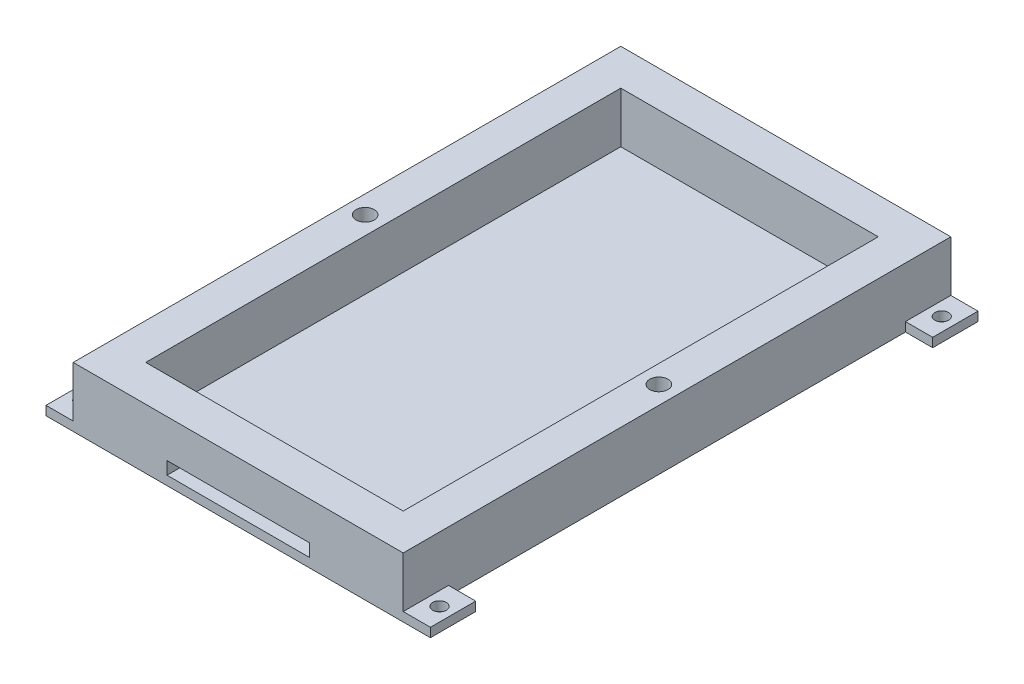
SolidWorks part; units mm, degrees
ref_plane "Plano frontal" through (0, 0, 0) normal (0, 0, 1) x (1, 0, 0)
ref_plane "Plano superior" through (0, 0, 0) normal (0, 1, 0) x (1, 0, 0)
ref_plane "Plano direito" through (0, 0, 0) normal (1, 0, 0) x (0, 0, -1)
sketch "Esboço1" plane through (0, 0, 0) normal (0, 1, 0) x (1, 0, 0)
  line L1 (-14.2, 26.2) -> (14.2, 26.2)
  line L2 (-14.2, 26.2) -> (-14.2, -26.2)
  line L3 (-14.2, -26.2) -> (14.2, -26.2)
  line L4 (14.2, 26.2) -> (14.2, -26.2)
  line L5 (-14.2, 26.2) -> (14.2, -26.2) construction
  line L6 (-14.2, -26.2) -> (14.2, 26.2) construction
  line L7 (-18.2, 30.2) -> (18.2, 30.2)
  line L8 (-18.2, 30.2) -> (-18.2, -30.2)
  line L9 (-18.2, -30.2) -> (18.2, -30.2)
  line L10 (18.2, 30.2) -> (18.2, -30.2)
  line L11 (-18.2, 30.2) -> (18.2, -30.2) construction
  line L12 (-18.2, -30.2) -> (18.2, 30.2) construction
  point P0 (0, 0)
  point P6 (0, 0)
  dimension "D1" = 52.4
  dimension "D2" = 28.4
  dimension "D3" = 60.4
  dimension "D4" = 36.4
extrude "Ressalto-extrusão1" add sketch "Esboço1" along normal blind 6.6
sketch "Esboço2" plane through (0, 0, 0) normal (0, 1, 0) x (1, 0, 0)
  line L1 (14.2, -26.2) -> (-14.2, -26.2)
  line L2 (14.2, -26.2) -> (14.2, 26.2)
  line L3 (14.2, 26.2) -> (-14.2, 26.2)
  line L4 (-14.2, -26.2) -> (-14.2, 26.2)
  line L5 (14.2, -26.2) -> (-14.2, 26.2) construction
  line L6 (14.2, 26.2) -> (-14.2, -26.2) construction
  point P0 (0, 0)
extrude "Ressalto-extrusão2" add sketch "Esboço2" along normal blind 1
sketch "Esboço3" plane through (0, 0, 30.2) normal (0, 0, 1) x (1, 0, 0)
  line L0 (-14.2, 1) -> (14.2, 1) construction
  line L1 (7.85, 1) -> (-7.85, 1)
  line L2 (7.85, 1) -> (7.85, 2.4)
  line L3 (7.85, 2.4) -> (-7.85, 2.4)
  line L4 (-7.85, 1) -> (-7.85, 2.4)
  dimension "D1" = 7.85
  dimension "D2" = 15.7
  dimension "D3" = 1.4
sketch "Esboço5" plane through (0, 0, 0) normal (0, 1, 0) x (1, 0, 0)
  line L1 (-18.2, 30.2) -> (-21.2, 30.2)
  line L2 (-18.2, 30.2) -> (-18.2, 25.2)
  line L3 (-18.2, 25.2) -> (-21.2, 25.2)
  line L4 (-21.2, 30.2) -> (-21.2, 25.2)
  line L5 (-18.2, -30.2) -> (-21.2, -30.2)
  line L6 (-18.2, -30.2) -> (-18.2, -25.2)
  line L7 (-18.2, -25.2) -> (-21.2, -25.2)
  line L8 (-21.2, -30.2) -> (-21.2, -25.2)
  line L9 (18.2, -30.2) -> (21.2, -30.2)
  line L10 (18.2, -30.2) -> (18.2, -25.2)
  line L11 (18.2, -25.2) -> (21.2, -25.2)
  line L12 (21.2, -30.2) -> (21.2, -25.2)
  line L13 (18.2, 30.2) -> (21.2, 30.2)
  line L14 (18.2, 30.2) -> (18.2, 25.2)
  line L15 (18.2, 25.2) -> (21.2, 25.2)
  line L16 (21.2, 30.2) -> (21.2, 25.2)
  circle A0 centre (-19.7, 27.7) radius 0.75
  circle A1 centre (19.7, 27.7) radius 0.75
  circle A2 centre (19.7, -27.7) radius 0.75
  circle A3 centre (-19.7, -27.7) radius 0.75
  point P30 (19.7, -27.7)
  dimension "D9" = 1.5
  dimension "D1" = 3
  dimension "D2" = 5
  dimension "D3" = 3
  dimension "D4" = 5
  dimension "D5" = 3
  dimension "D6" = 3
  dimension "D7" = 5
  dimension "D8" = 5
extrude "Ressalto-extrusão3" add sketch "Esboço5" along normal blind 1
sketch "Esboço6" plane through (0, 6.6, 0) normal (0, 1, 0) x (1, 0, 0)
  circle A2 centre (-16.2, 0) radius 1
  circle A3 centre (16.2, 0) radius 1
  point P6 (16.2, 0)
  dimension "D3" = 2
  dimension "D4" = 2
extrude "Corte-extrusão3" cut sketch "Esboço6" against normal blind 4
extrude "Corte-extrusão4" cut sketch "Esboço3" against normal blind 5
